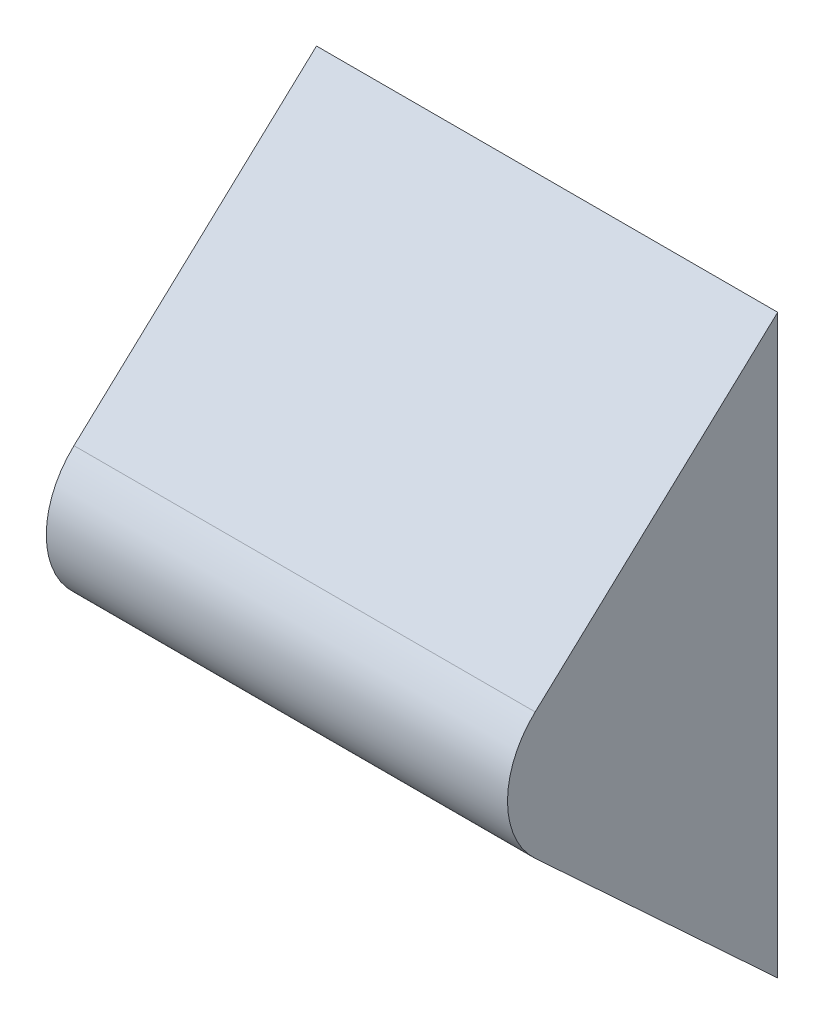
SolidWorks part; units mm, degrees
ref_plane "Alzado" through (0, 0, 0) normal (0, 0, 1) x (1, 0, 0)
ref_plane "Planta" through (0, 0, 0) normal (0, 1, 0) x (1, 0, 0)
ref_plane "Vista lateral" through (0, 0, 0) normal (1, 0, 0) x (0, 0, -1)
sketch "Croquis1" plane through (0, 0, 0) normal (1, 0, 0) x (0, -1, 0)
  line L0 (-11, -10.198) -> (-50, 31.8689)
  line L1 (11, -10.198) -> (50, 31.8689)
  line L2 (-11, -10.198) -> (11, -10.198) construction
  line L4 (-50, 31.8689) -> (50, 31.8689)
  arc A0 (-11, -10.198) -> (11, -10.198) centre (0, 0) ccw
  dimension "D1" = 30
  dimension "D2" = 50
  dimension "D3" = 50
  dimension "D4" = 22
extrude "Saliente-Extruir1" add sketch "Croquis1" along normal mid plane 80
